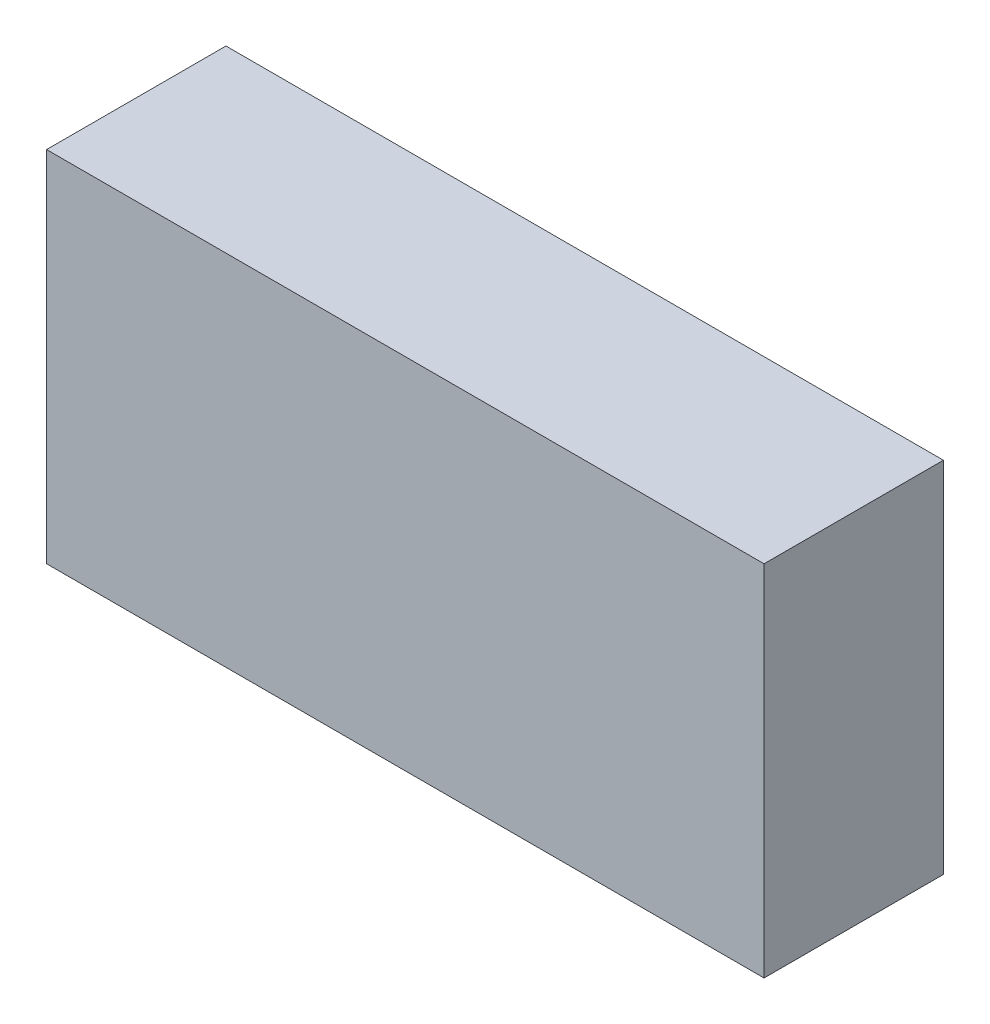
SolidWorks part; units mm, degrees
ref_plane "Plane1" through (0, 0, 0) normal (0, 0, 1) x (1, 0, 0)
ref_plane "Plane2" through (0, 0, 0) normal (0, 1, 0) x (1, 0, 0)
ref_plane "Plane3" through (0, 0, 0) normal (1, 0, 0) x (0, 0, -1)
sketch "Sketch1" plane through (0, 0, 0) normal (0, 0, 1) x (1, 0, 0)
  line L1 (0, 0) -> (203.2, 0)
  line L2 (0, 0) -> (0, 101.6)
  line L3 (0, 101.6) -> (203.2, 101.6)
  line L4 (203.2, 0) -> (203.2, 101.6)
  dimension "D1" = 203.2
  dimension "D2" = 101.6
extrude "Extrude1" add sketch "Sketch1" along normal blind 50.8
sketch "Sketch2" plane through (0, 0, 50.8) normal (0, 0, 1) x (1, 0, 0)
  line L0 (83.0232, 99.06) -> (89.3732, 99.06)
  line L2 (157.48, 83.82) -> (157.48, 78.74)
  line L3 (157.48, 78.74) -> (91.44, 78.74)
  line L4 (91.44, 78.74) -> (83.0232, 99.06)
  line L5 (203.2, 101.6) -> (0, 101.6) construction
  line L6 (0, 101.6) -> (0, 0) construction
  line L7 (157.48, 83.82) -> (102.4931, 88.7077)
  line L8 (98.7377, 90.3765) -> (89.3732, 99.06)
  arc A0 (98.7377, 90.3765) -> (102.4931, 88.7077) centre (103.0553, 95.0328) ccw
  point P12 (100.33, 88.9)
  dimension "D10" = 6.35
  dimension "D1" = 67.5
  dimension "D2" = 20.32
  dimension "D3" = 2.54
  dimension "D4" = 5.08
  dimension "D5" = 66.04
  dimension "D6" = 157.48
  dimension "D7" = 6.35
  dimension "D8" = 57.15
  dimension "D9" = 5.08
sketch "Sketch4" plane through (0, 0, 50.8) normal (0, 0, 1) x (1, 0, 0)
  line L0 (86.5799, 90.4733) -> (72.5, 84.6412)
  line L1 (91.44, 78.74) -> (83.0232, 99.06) construction
  line L2 (72.5, 84.6412) -> (69.6673, 84.8425)
  line L3 (69.6673, 84.8425) -> (73.0694, 76.6292)
  line L4 (73.0694, 76.6292) -> (74.93, 78.7745)
  line L5 (74.93, 78.7745) -> (89.01, 84.6066)
  line L6 (89.01, 84.6066) -> (91.8426, 84.4053)
  line L7 (91.8426, 84.4053) -> (88.4406, 92.6186)
  line L8 (88.4406, 92.6186) -> (86.5799, 90.4733)
  dimension "D1" = 6.35
  dimension "D2" = 8.89
  dimension "D3" = 1.27
  dimension "D4" = 8.89
  dimension "D5" = 1.27
  dimension "D6" = 2.54
  dimension "D7" = 2.54
  dimension "D8" = 15.24
  dimension "D9" = 6.35
sketch "Sketch5" plane through (0, 0, 50.8) normal (0, 0, 1) x (1, 0, 0)
  line L0 (69.7842, 91.1978) -> (77.5603, 72.4245)
  line L1 (77.5603, 72.4245) -> (43.4353, 38.2996)
  line L2 (43.4353, 38.2996) -> (23.4233, 51.0486)
  line L5 (23.4233, 51.0486) -> (30.1436, 56.8684)
  line L6 (157.48, 78.74) -> (91.44, 78.74) construction
  line L7 (30.1436, 56.8684) -> (37.6275, 52.1007)
  line L8 (45.5295, 52.9661) -> (64.4212, 71.8578)
  line L9 (65.7977, 78.778) -> (63.0639, 85.3779)
  line L10 (63.0639, 85.3779) -> (69.7842, 91.1978)
  arc A0 (37.6275, 52.1007) -> (45.5295, 52.9661) centre (41.0393, 57.4562) ccw
  arc A1 (65.7977, 78.778) -> (64.4212, 71.8578) centre (59.9311, 76.3479) cw
  point P14 (41.9258, 49.3624)
  dimension "D10" = 6.35
  dimension "D1" = 135
  dimension "D2" = 6.35
  dimension "D3" = 8.89
  dimension "D4" = 48.26
  dimension "D5" = 102.5
  dimension "D6" = 8.89
  dimension "D7" = 20.32
  dimension "D8" = 8.89
  dimension "D9" = 13.97
sketch "Sketch6" plane through (0, 0, 50.8) normal (0, 0, 1) x (1, 0, 0)
  line L0 (31.6531, 45.8056) -> (23.4647, 32.9524)
  line L1 (43.4353, 38.2996) -> (23.4233, 51.0486) construction
  line L2 (23.4647, 32.9524) -> (21.0288, 31.4925)
  line L3 (21.0288, 31.4925) -> (26.3844, 28.0807)
  line L4 (26.3844, 28.0807) -> (26.678, 30.9052)
  line L5 (26.678, 30.9052) -> (34.8665, 43.7585)
  line L6 (34.8665, 43.7585) -> (37.3023, 45.2184)
  line L7 (37.3023, 45.2184) -> (31.9468, 48.6302)
  line L9 (31.9468, 48.6302) -> (31.6531, 45.8056)
  dimension "D1" = 3.81
  dimension "D2" = 6.35
  dimension "D3" = 6.35
  dimension "D4" = 1.27
  dimension "D5" = 1.27
  dimension "D6" = 2.54
  dimension "D7" = 2.54
  dimension "D8" = 15.24
  dimension "D9" = 10.16
sketch "Sketch8" plane through (0, 0, 50.8) normal (0, 0, 1) x (1, 0, 0)
  line L0 (16.648, 37.2951) -> (33.1047, 26.811)
  line L1 (33.1047, 26.811) -> (26.5892, 8.9099)
  line L2 (26.5892, 8.9099) -> (2.721, 17.5972)
  line L3 (16.648, 37.2951) -> (10.6809, 39.4669)
  line L4 (2.721, 17.5972) -> (10.6809, 39.4669)
  line L8 (43.4353, 38.2996) -> (23.4233, 51.0486) construction
  dimension "D1" = 7.62
  dimension "D2" = 102.5
  dimension "D3" = 25.4
  dimension "D4" = 19.05
  dimension "D5" = 6.35
sketch "Sketch14" plane through (0, 0, 50.8) normal (0, 0, 1) x (1, 0, 0)
  line L0 (157.48, 78.74) -> (91.44, 78.74) construction
  line L1 (93.98, 80.772) -> (154.94, 80.772)
  line L2 (93.98, 80.772) -> (93.98, 74.422)
  line L3 (93.98, 74.422) -> (154.94, 74.422)
  line L4 (154.94, 80.772) -> (154.94, 74.422)
  line L5 (157.48, 83.82) -> (157.48, 78.74) construction
  dimension "D1" = 2.032
  dimension "D2" = 2.54
  dimension "D3" = 2.54
  dimension "D4" = 6.35
sketch "Sketch15" plane through (0, 0, 50.8) normal (0, 0, 1) x (1, 0, 0)
  line L0 (43.7945, 41.5325) -> (48.2847, 37.0423)
  line L2 (48.2847, 37.0423) -> (78.8175, 67.5752)
  line L3 (78.8175, 67.5752) -> (74.3274, 72.0653)
  line L4 (74.3274, 72.0653) -> (43.7945, 41.5325)
  line L5 (77.5603, 72.4245) -> (43.4353, 38.2996) construction
  dimension "D1" = 2.032
  dimension "D2" = 2.54
  dimension "D3" = 6.35
  dimension "D4" = 2.54
sketch "Sketch16" plane through (0, 0, 50.8) normal (0, 0, 1) x (1, 0, 0)
  line L0 (25.5485, 11.9917) -> (31.5155, 9.8199)
  line L1 (31.5155, 9.8199) -> (36.2935, 22.9474)
  line L2 (36.2935, 22.9474) -> (30.3265, 25.1192)
  line L3 (30.3265, 25.1192) -> (25.5485, 11.9917)
  line L4 (33.1047, 26.811) -> (26.5892, 8.9099) construction
  dimension "D1" = 2.032
  dimension "D2" = 6.35
  dimension "D3" = 2.54
  dimension "D4" = 2.54
sketch "Sketch19" plane through (0, 0, 50.8) normal (0, 0, 1) x (1, 0, 0)
  line L0 (155.194, 72.39) -> (86.506, 72.39)
  line L1 (86.506, 72.39) -> (45.2314, 31.1154)
  line L2 (45.2314, 31.1154) -> (113.9194, 31.1154)
  line L3 (113.9194, 31.1154) -> (155.194, 72.39)
  line L4 (93.98, 74.422) -> (154.94, 74.422) construction
  line L5 (48.2847, 37.0423) -> (78.8175, 67.5752) construction
  line L7 (43.7945, 41.5325) -> (48.2847, 37.0423) construction
  line L8 (154.94, 80.772) -> (154.94, 74.422) construction
  dimension "D1" = 2.032
  dimension "D2" = 2.032
  dimension "D3" = 6.35
  dimension "D4" = 0.254
